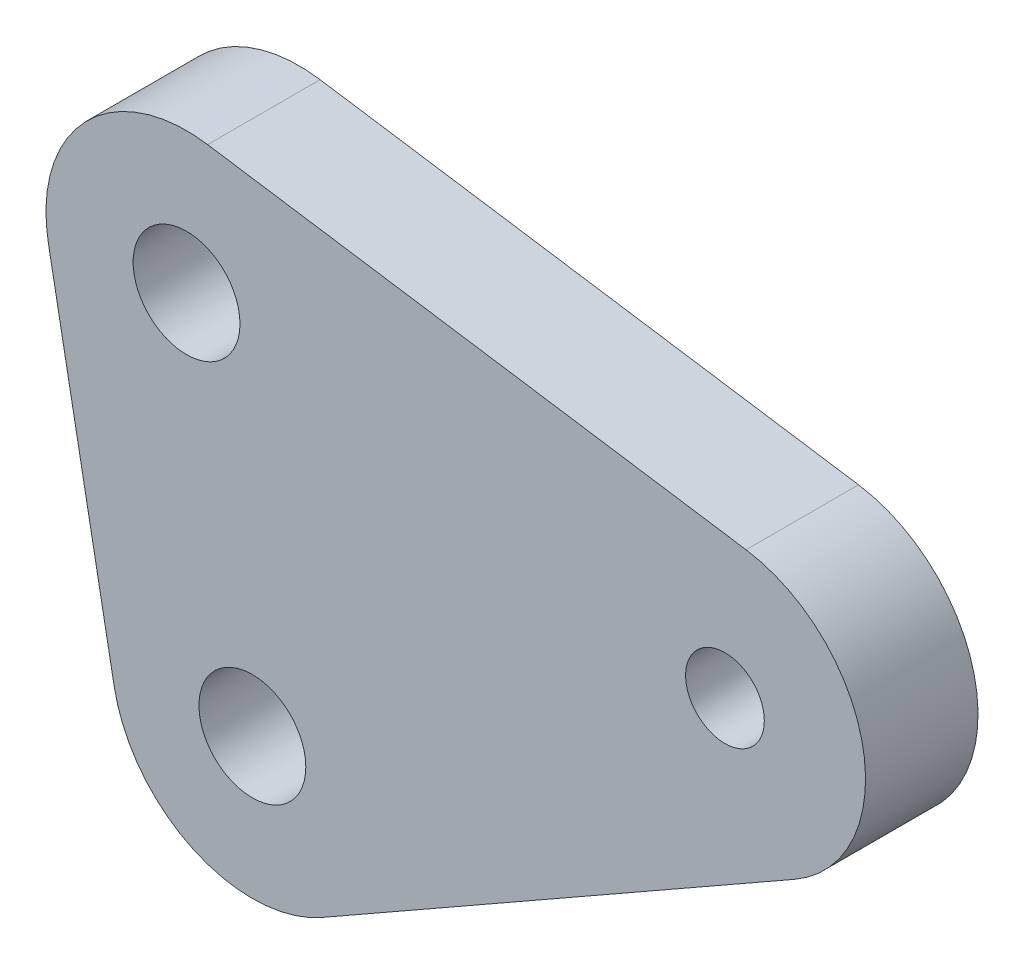
SolidWorks part; units mm, degrees
ref_plane "Front Plane" through (0, 0, 0) normal (0, 0, 1) x (1, 0, 0)
ref_plane "Top Plane" through (0, 0, 0) normal (0, 1, 0) x (1, 0, 0)
ref_plane "Right Plane" through (0, 0, 0) normal (1, 0, 0) x (0, 0, -1)
sketch "Sketch1" plane through (0, 0, 0) normal (0, 0, 1) x (1, 0, 0)
  line L0 (143.3333, 493) -> (716.6667, 493) construction
  line L6 (26.1417, 72.0991) -> (28.4826, 59.6183) construction
  line L7 (26.8916, 77.0426) -> (46.038, 74.1382)
  line L8 (30.958, 55.2742) -> (47.7636, 64.8506)
  line L9 (21.2274, 71.1774) -> (23.5682, 58.6966)
  circle A3 centre (26.1417, 72.0991) radius 1.9
  circle A4 centre (28.4826, 59.6183) radius 1.9
  circle A5 centre (45.2881, 69.1948) radius 1.4
  arc A13 (47.7636, 64.8506) -> (46.038, 74.1382) centre (45.2881, 69.1948) ccw
  arc A14 (26.8916, 77.0426) -> (21.2274, 71.1774) centre (26.1417, 72.0991) ccw
  arc A15 (23.5682, 58.6966) -> (30.958, 55.2742) centre (28.4826, 59.6183) ccw
extrude "Boss-Extrude1" add sketch "Sketch1" along normal blind 4
